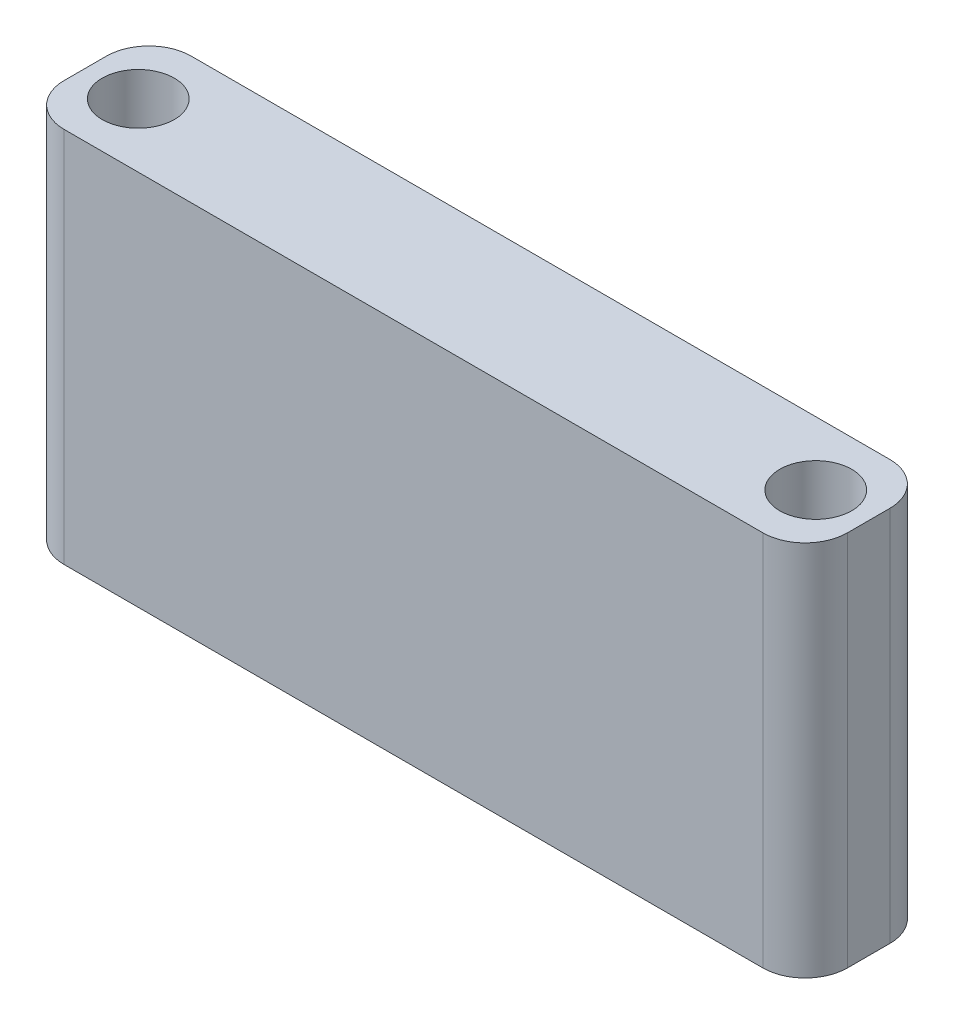
SolidWorks part; units mm, degrees
ref_plane "Alzado" through (0, 0, 0) normal (0, 0, 1) x (1, 0, 0)
ref_plane "Planta" through (0, 0, 0) normal (0, 1, 0) x (1, 0, 0)
ref_plane "Vista lateral" through (0, 0, 0) normal (1, 0, 0) x (0, 0, -1)
sketch "Croquis1" plane through (0, 0, 0) normal (0, 1, 0) x (1, 0, 0)
  line L0 (0, 3) -> (37, 3) construction
  line L1 (0, 0) -> (37, 0)
  line L2 (0, 0) -> (0, 6)
  line L3 (0, 6) -> (37, 6)
  line L4 (37, 0) -> (37, 6)
  circle A0 centre (2.5, 3) radius 1.7
  circle A1 centre (34.5, 3) radius 1.7
  dimension "D3" = 3.4
  dimension "D1" = 37
  dimension "D2" = 6
  dimension "D4" = 32
  dimension "D5" = 2.5
extrude "Saliente-Extruir1" add sketch "Croquis1" along normal blind 17.8
fillet "Redondeo1" radius 2 4 edges at (0, 8.9, 0) (0, 8.9, -6) (37, 8.9, 0) (37, 8.9, -6)
